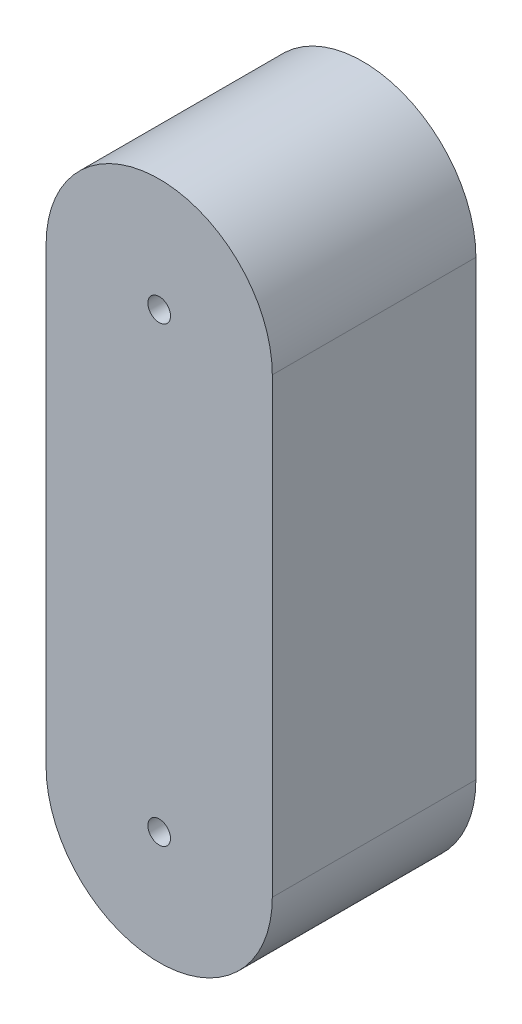
SolidWorks part; units mm, degrees
ref_plane "Ebene vorne" through (0, 0, 0) normal (0, 0, 1) x (1, 0, 0)
ref_plane "Ebene oben" through (0, 0, 0) normal (0, 1, 0) x (1, 0, 0)
ref_plane "Ebene rechts" through (0, 0, 0) normal (1, 0, 0) x (0, 0, -1)
sketch "Skizze1" plane through (0, 0, 0) normal (0, 0, 1) x (1, 0, 0)
  line L0 (0, 0) -> (0, 200) construction
  line L1 (-50, 200) -> (-50, 0)
  line L2 (50, 0) -> (50, 200)
  arc A0 (-50, 0) -> (50, 0) centre (0, 0) ccw
  arc A1 (50, 200) -> (-50, 200) centre (0, 200) ccw
  circle A2 centre (0, 0) radius 5
  circle A3 centre (0, 200) radius 5
  dimension "D2" = 100
  dimension "D3" = 100
  dimension "D1" = 200
extrude "Aufsatz-Linear austragen1" add sketch "Skizze1" along normal blind 90
